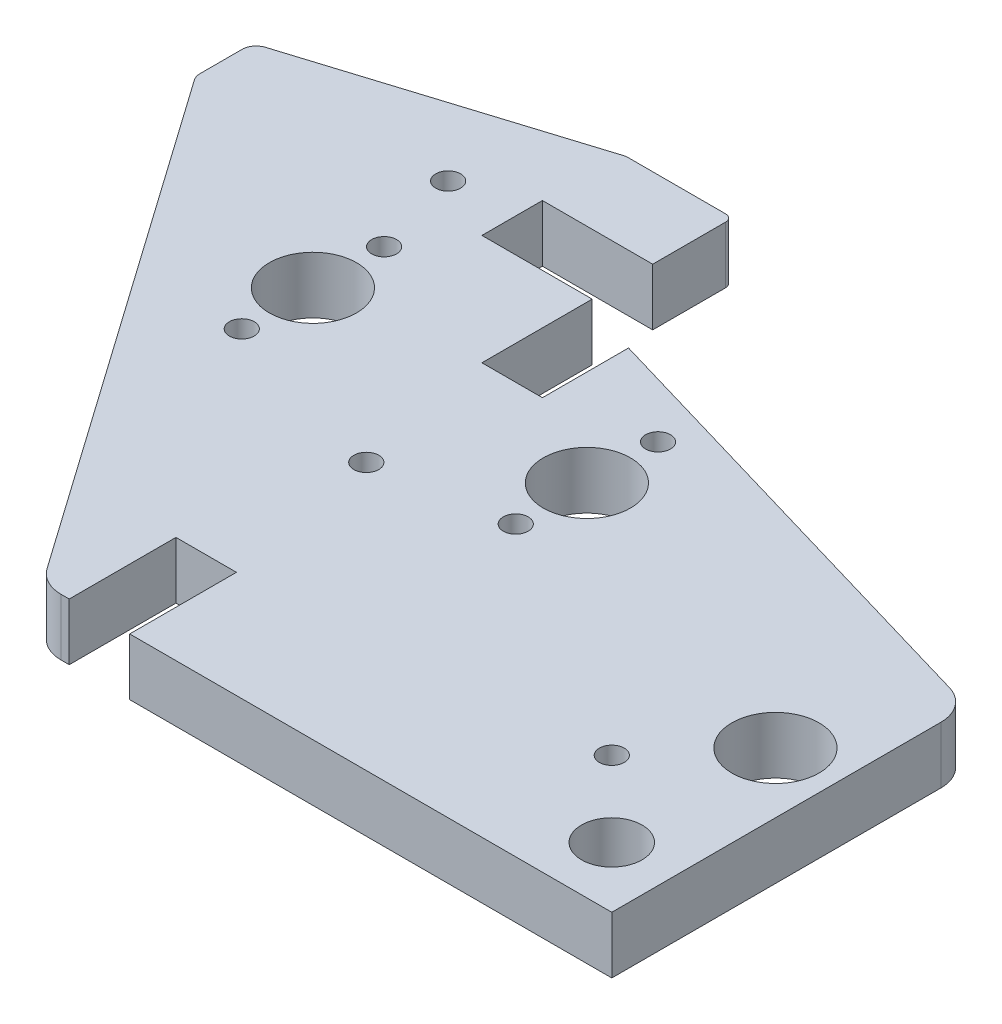
SolidWorks part; units mm, degrees
ref_plane "Front Plane" through (0, 0, 0) normal (0, 0, 1) x (1, 0, 0)
ref_plane "Top Plane" through (0, 0, 0) normal (0, 1, 0) x (1, 0, 0)
ref_plane "Right Plane" through (0, 0, 0) normal (1, 0, 0) x (0, 0, -1)
sketch "Sketch1" plane through (0, 0, 0) normal (0, 1, 0) x (1, 0, 0)
  line L0 (135.9054, 28.3918) -> (135.9054, 74.6506)
  line L1 (132.3163, 79.4475) -> (67.9054, 98.3918)
  line L2 (67.9054, 98.3918) -> (59.9054, 100.7448)
  line L8 (59.9054, 109.8918) -> (59.9054, 120.3918)
  line L9 (58.9054, 121.3918) -> (45.2107, 121.3918)
  line L10 (44.6141, 121.3008) -> (6.3089, 109.3304)
  line L11 (4.9054, 107.4214) -> (4.9054, 101.5248)
  line L12 (5.2696, 100.3741) -> (54.4118, 30.5151)
  line L13 (58.5014, 28.3918) -> (59.9054, 28.3918)
  line L17 (67.9054, 28.3918) -> (135.9054, 28.3918)
  line L18 (59.9054, 109.8918) -> (59.9054, 100.7448)
  line L20 (59.9054, 28.3918) -> (67.9054, 28.3918)
  arc A0 (135.9054, 74.6506) -> (132.3163, 79.4475) centre (130.9054, 74.6506) ccw
  arc A1 (59.9054, 120.3918) -> (58.9054, 121.3918) centre (58.9054, 120.3918) ccw
  arc A2 (45.2107, 121.3918) -> (44.6141, 121.3008) centre (45.2107, 119.3918) ccw
  arc A3 (6.3089, 109.3304) -> (4.9054, 107.4214) centre (6.9054, 107.4214) ccw
  arc A4 (4.9054, 101.5248) -> (5.2696, 100.3741) centre (6.9054, 101.5248) ccw
  arc A5 (54.4118, 30.5151) -> (58.5014, 28.3918) centre (58.5014, 33.3918) ccw
  circle A6 centre (127.4054, 59.8918) radius 6.125
  circle A7 centre (127.4054, 36.8918) radius 4.25
  circle A8 centre (116.7988, 47.4984) radius 1.75
  circle A9 centre (81.9054, 78.8918) radius 6.125
  circle A10 centre (81.9054, 88.8918) radius 1.75
  circle A11 centre (81.9054, 68.8918) radius 1.75
  circle A12 centre (38.9054, 83.3918) radius 6.125
  circle A13 centre (38.9054, 93.3918) radius 1.75
  circle A14 centre (38.9054, 73.3918) radius 1.75
  circle A15 centre (35.4054, 105.8918) radius 1.75
  circle A16 centre (63.9054, 65.8918) radius 1.75
  dimension "D1" = 12.25
  dimension "D2" = 8.5
  dimension "D3" = 19.1066
  dimension "D4" = 8.5
  dimension "D5" = 8.5
  dimension "D6" = 8.5
  dimension "D7" = 23
extrude "Extrude1" add sketch "Sketch1" along normal blind 8
sketch "Sketch3" plane through (0, 8, 0) normal (0, 1, 0) x (1, 0, 0)
  line L0 (58.5014, 28.3918) -> (135.9054, 28.3918) construction
  line L1 (68.1554, 28.3918) -> (59.6554, 28.3918)
  line L2 (68.1554, 28.3918) -> (68.1554, 43.3918)
  line L3 (68.1554, 43.3918) -> (59.6554, 43.3918)
  line L4 (59.6554, 28.3918) -> (59.6554, 43.3918)
  line L5 (68.1554, 43.3918) -> (59.6554, 28.3918) construction
  line L6 (135.9054, 28.3918) -> (135.9054, 74.6506) construction
  line L7 (59.9054, 100.7448) -> (59.9054, 120.3918) construction
  line L8 (59.9054, 110.1418) -> (44.4054, 110.1418)
  line L9 (59.9054, 110.1418) -> (59.9054, 101.6418)
  line L10 (59.9054, 101.6418) -> (44.4054, 101.6418)
  line L11 (44.4054, 110.1418) -> (44.4054, 101.6418)
  line L12 (44.4054, 101.6418) -> (59.9054, 110.1418) construction
  line L13 (58.9054, 121.3918) -> (45.2107, 121.3918) construction
  line L15 (59.9054, 101.6418) -> (68.4054, 101.6418)
  line L16 (59.9054, 101.6418) -> (59.9054, 86.1418)
  line L17 (59.9054, 86.1418) -> (68.4054, 86.1418)
  line L18 (68.4054, 101.6418) -> (68.4054, 86.1418)
  point P6 (63.9054, 35.8918)
  point P15 (52.1554, 105.8918)
  dimension "D1" = 8.5
  dimension "D2" = 15
  dimension "D3" = 72
  dimension "D4" = 8.5
  dimension "D5" = 15.5
  dimension "D6" = 15.5
  dimension "D7" = 15.5
  dimension "D8" = 8.5
extrude "Extrude2" cut sketch "Sketch3" against normal blind 10 contours L10 L11 L8 L9 | L16 L17 L18 L15 | L2 L3 L4 L1
